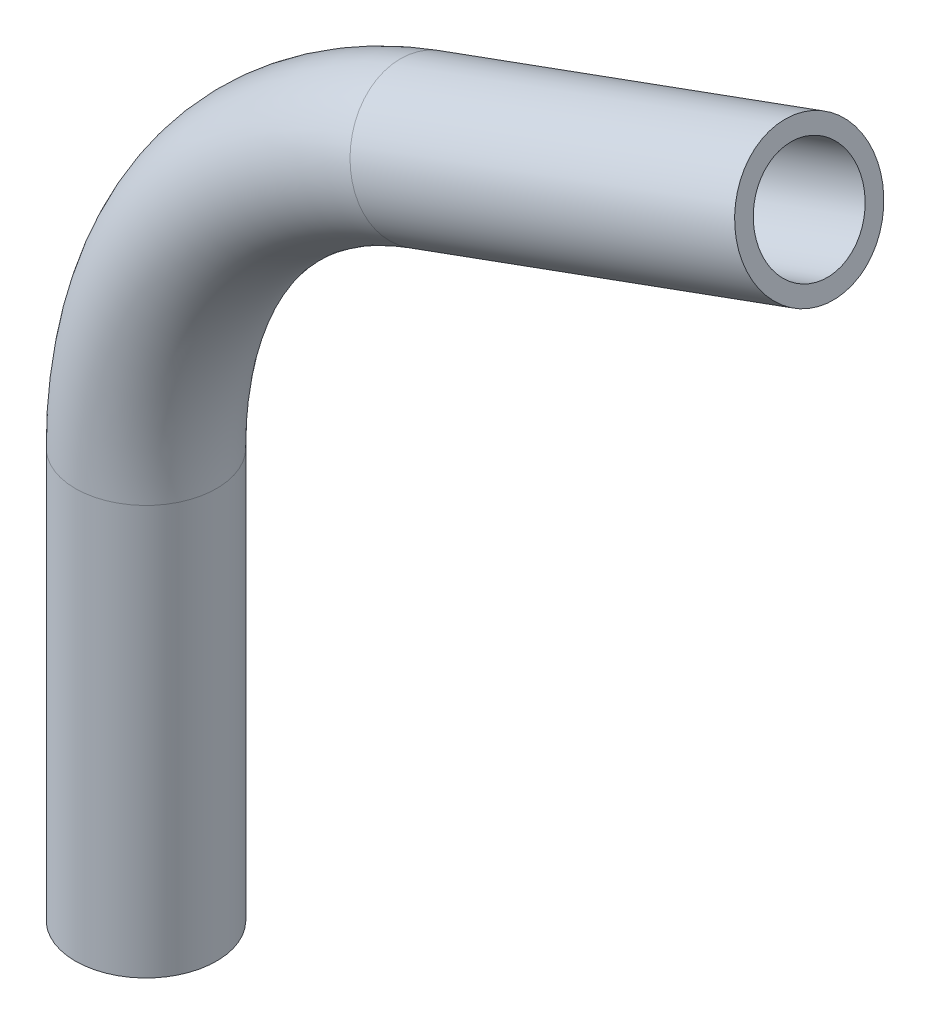
SolidWorks part; units mm, degrees
ref_plane "Front Plane" through (0, 0, 0) normal (0, 0, 1) x (1, 0, 0)
ref_plane "Top Plane" through (0, 0, 0) normal (0, 1, 0) x (1, 0, 0)
ref_plane "Right Plane" through (0, 0, 0) normal (1, 0, 0) x (0, 0, -1)
sketch "Sketch1" plane through (0, 0, 0) normal (0, 0, 1) x (1, 0, 0)
  line L0 (0, 0) -> (0, 23.195)
  line L1 (15.7915, 45.7476) -> (37.5877, 53.6808)
  arc A0 (0, 23.195) -> (15.7915, 45.7476) centre (24, 23.195) cw
  point P6 (0, 40)
  dimension "D3" = 24
  dimension "D1" = 40
  dimension "D2" = 40
  dimension "D4" = 110
sketch "Sketch2" plane through (0, 0, 0) normal (0, 1, 0) x (1, 0, 0)
  circle A0 centre (0, 0) radius 4
  circle A1 centre (0, 0) radius 3
  dimension "D1" = 6
  dimension "D2" = 8
sweep "Sweep1" add profiles "Sketch2" path "Sketch1"
